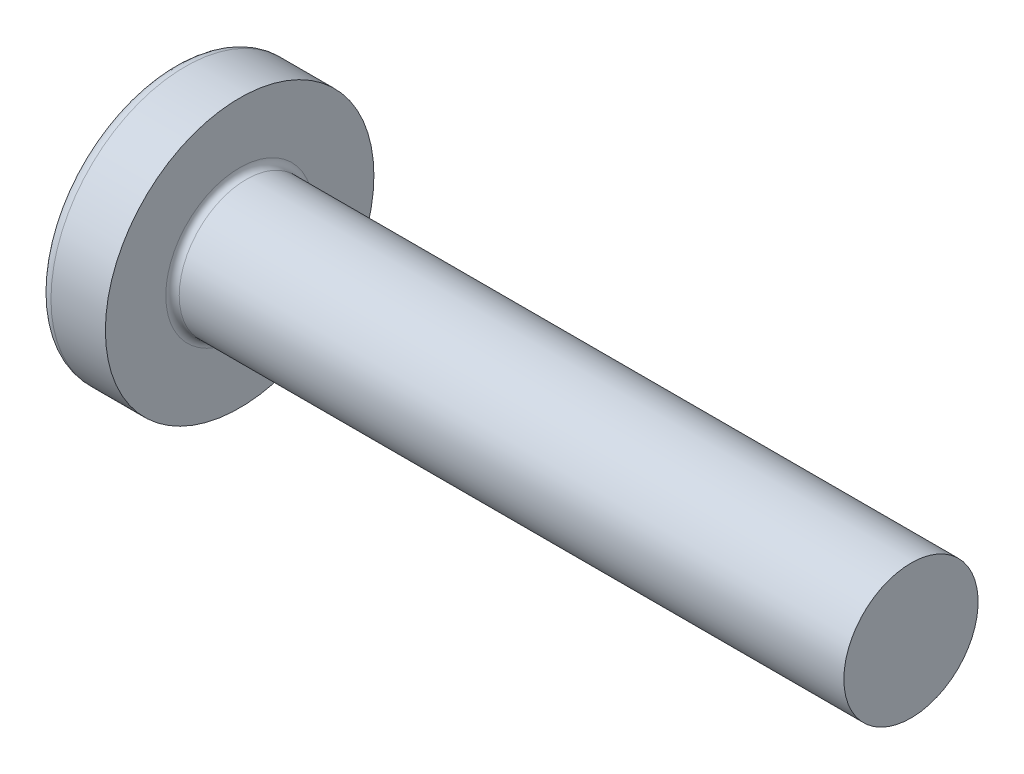
SolidWorks part; units mm, degrees
ref_plane "Plane1" through (0, 0, 0) normal (0, 0, 1) x (1, 0, 0)
ref_plane "Plane2" through (0, 0, 0) normal (0, 1, 0) x (1, 0, 0)
ref_plane "Plane3" through (0, 0, 0) normal (1, 0, 0) x (0, 0, -1)
sketch "BodySke" plane through (0, 0, 0) normal (0, 0, 1) x (1, 0, 0)
  line L0 (1.6, 1) -> (1.6, 2)
  line L1 (1.8, 6.35) -> (1.8, -3.175) construction
  line L2 (-25.4, 0) -> (127, 0) construction
  line L3 (11.6, 0) -> (0, 0)
  line L4 (1.6, 1) -> (11.6, 1)
  line L5 (11.6, 1) -> (11.6, 0)
  line L6 (0.79, 2) -> (1.6, 2)
  line L8 (1.6, 6.35) -> (1.6, -3.175) construction
  arc A0 (0.6464, 1.9285) -> (0, 0) centre (3.2, 0) ccw
  arc A2 (0.6464, 1.9285) -> (0.79, 2) centre (0.79, 1.82) cw
  dimension "Head_crown_rad" = 3.2
  dimension "Head_fillet_rad" = 0.18
  dimension "Length" = 10
  dimension "Head_ht" = 1.6
  dimension "Head_dia" = 4
  dimension "Advance" = 0.4
  dimension "Thread_nom" = 10
  dimension "Diameter" = 2
revolve "Base-Revolve" add sketch "BodySke"
cosmetic thread "ThreadCosmetic" [suppressed]
fillet "Fillet1" radius 0.1 1 edges at (1.6, 0, 1)
sketch "Sketch3" plane through (0, 0, 0) normal (1, 0, 0) x (0, 0, -1)
  line L0 (0.24, -1.05) -> (-0.24, -1.05)
  line L1 (0.24, -1.05) -> (0.24, 1.05)
  line L2 (-0.24, 1.05) -> (0.24, 1.05)
  line L3 (-0.24, 1.05) -> (-0.24, -1.05)
  dimension "Cross_dia" = 2.1
  dimension "D1" = 1.05
  dimension "Cross_width" = 0.48
  dimension "D2" = 0.24
ref_plane "Plane4" through (1.42, 0, 0) normal (1, 0, 0) x (0, 0, -1)
sketch "Sketch4" plane through (1.42, 0, 0) normal (1, 0, 0) x (0, 0, -1)
  line L0 (0.24, -0.342) -> (-0.24, -0.342)
  line L1 (0.24, -0.342) -> (0.24, 0.342)
  line L2 (-0.24, 0.342) -> (0.24, 0.342)
  line L3 (-0.24, 0.342) -> (-0.24, -0.342)
  dimension "D1" = 0.48
  dimension "D2" = 0.684
  dimension "D3" = 0.24
  dimension "D4" = 0.342
loft "Recess" cut profiles "Sketch3", "Sketch4"
pattern_circular "RecPat" count 2 every 90 about axis through (0, 0, 0) along (1, 0, 0) of "Recess"
sketch "RecCorSke" plane through (0, 0, 0) normal (0, 0, 1) x (1, 0, 0)
  line L0 (-3.175, 0) -> (15.875, 0) construction
  line L1 (-25.4, 0) -> (127, 0) construction
  line L2 (0, 0) -> (0, 0.4548)
  line L3 (0, 0.4548) -> (1.42, 0.3555)
  line L4 (1.42, 0.3555) -> (1.5355, 0)
  line L5 (1.5355, 0) -> (0, 0)
  dimension "Diameter" = 0.711
  dimension "Depth" = 1.42
  dimension "Draft_angle" = 4
  dimension "Bottom_angle" = 18
revolve "RecessCore" cut sketch "RecCorSke" angle 360 about L0
sketch "ThdSchSke" plane through (0, 0, 0) normal (0, 0, 1) x (1, 0, 0)
  line L0 (2.4, -0.774) -> (2.2418, -1)
  line L1 (2.4, -0.774) -> (2.5582, -1)
  line L2 (2.5582, -1) -> (2.5582, -1.25)
  line L3 (-3.175, 0) -> (5.1513, 0) construction
  line L5 (2.5582, -1.25) -> (2.2418, -1.25)
  line L6 (2.2418, -1.25) -> (2.2418, -1)
  dimension "Diameter" = 2
  dimension "SideAngle" = 55
  dimension "VeeAngle" = 70
  dimension "Thread_minor" = 1.548
  dimension "Overcut" = 2.5
  dimension "Start" = 2.4
revolve "ThreadSchematic" [suppressed] cut sketch "ThdSchSke" angle 360 about L3
pattern_linear "ThdSchPat" [suppressed]
equation "\"D1@Sketch3\" = \"Cross_dia@Sketch3\" / 2"
equation "\"D2@Sketch3\" = \"Cross_width@Sketch3\" / 2"
equation "\"Depth@RecCorSke\" = \"Cross_depth@Plane4\""
equation "\"D1@Sketch4\" = \"Cross_width@Sketch3\""
equation "\"D2@Sketch4\" = \"Cross_dia@Sketch3\" - 2.0 * \"Cross_depth@Plane4\" * tan(26.5  * 0.017453292)"
equation "\"D3@Sketch4\" = \"D1@Sketch4\" / 2"
equation "\"D4@Sketch4\" = \"D2@Sketch4\" / 2"
equation "\"Thread_length@ThreadCosmetic\" = ((sgn( (\"Length@BodySke\" - \"Advance@BodySke\" * 2.0 ) - \"Thread_nom@BodySke\" )-1)*( (\"Length@BodySke\" - \"Advance@BodySke\" * 2.0 ) - \"Thread_nom@BodySke\" ))/-2+ \"Thread_nom@BodySke\""
equation "\"Thread_minor@ThdSchSke\" = \"Thread_minor@ThreadCosmetic\""
equation "\"Diameter@ThdSchSke\" = \"Diameter@BodySke\""
equation "\"Overcut@ThdSchSke\" = \"Diameter@BodySke\" * 1.25"
equation "\"Start@ThdSchSke\" = \"Head_ht@BodySke\" + \"Length@BodySke\" - \"Thread_length@ThreadCosmetic\"  '---Non-countersunk---"
equation "\"Num_threads@ThdSchPat\" = int( \"Thread_length@ThreadCosmetic\" / \"Advance@BodySke\" + 0.999 )  + 1"
equation "\"Advance@ThdSchPat\" = \"Thread_length@ThreadCosmetic\" /  (\"Num_threads@ThdSchPat\" - 1) 'relax it"
